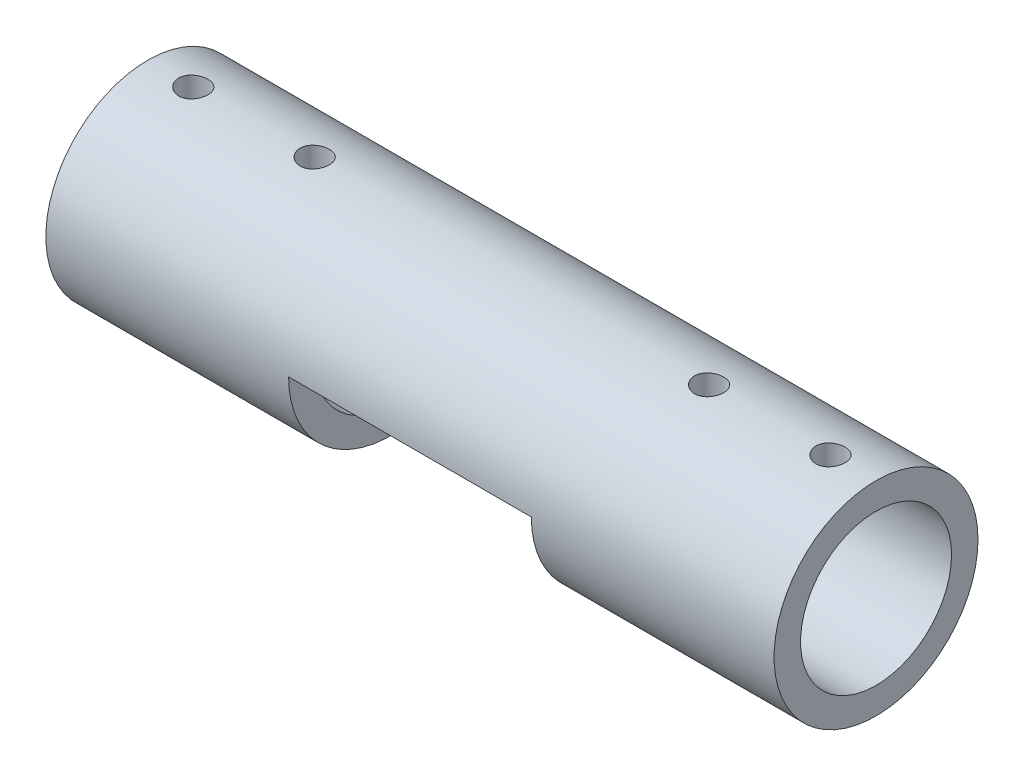
SolidWorks part; units mm, degrees
ref_plane "Front Plane" through (0, 0, 0) normal (0, 0, 1) x (1, 0, 0)
ref_plane "Top Plane" through (0, 0, 0) normal (0, 1, 0) x (1, 0, 0)
ref_plane "Right Plane" through (0, 0, 0) normal (1, 0, 0) x (0, 0, -1)
sketch "Sketch1" plane through (0, 0, 0) normal (1, 0, 0) x (0, 0, -1)
  circle A0 centre (0, 0) radius 10.668
  circle A1 centre (0, 0) radius 7.8994
  dimension "D2" = 15.7988
  dimension "D1" = 21.336
extrude "MainBody" add sketch "Sketch1" along normal blind 76.2
sketch "Sketch2" plane through (0, 0, 0) normal (0, 1, 0) x (1, 0, 0)
  line L1 (25.4, 12.7) -> (50.8, 12.7)
  line L2 (25.4, 12.7) -> (25.4, -12.7)
  line L3 (25.4, -12.7) -> (50.8, -12.7)
  line L4 (50.8, 12.7) -> (50.8, -12.7)
  point P7 (38.1, 12.7)
  point P8 (50.8, 0)
  dimension "D3" = 38.1
  dimension "D4" = 25.4
  dimension "D5" = 25.4
extrude "CoaxEntry" cut sketch "Sketch2" against normal up to surface up to face at (76.2, 0, -10.668)
sketch "Sketch3" plane through (0, 0, 0) normal (0, 1, 0) x (1, 0, 0)
  line L0 (76.2, -10.668) -> (76.2, 10.668) construction
  circle A0 centre (4.7625, 0) radius 1.524
  circle A2 centre (17.4625, 0) radius 1.524
  circle A3 centre (71.4375, 0) radius 1.524
  circle A4 centre (58.7375, 0) radius 1.524
  point P3 (0, 0)
  dimension "D1" = 3.048
  dimension "D2" = 4.7625
  dimension "D4" = 12.7
  dimension "D5" = 4.7625
  dimension "D3" = 2
extrude "AntennaMountHoles" cut sketch "Sketch3" along normal through all
equation "\"OD\" = 0.84in'Outer Diameter of PVC (1/2in Sch 40)"
equation "\"D1@Sketch1\"=\"OD\""
equation "\"ID\" = 0.622in'Inner Diameter of PCV (1/2in Sch 40)"
equation "\"D2@Sketch1\"=\"ID\""
equation "\"PVC_Len\" = 3in'Length of PVC to make connector"
equation "\"D1@MainBody\" = \"PVC_Len\""
equation "\"Max_Coax_Diam\"=1"
equation "\"ScrewDiam\"=0.12"
equation "\"D1@Sketch3\"=\"ScrewDiam\""
equation "\"AntennaScrew_Inset\"=0.1875"
equation "\"D2@Sketch3\"=\"AntennaScrew_Inset\""
equation "\"D5@Sketch3\"=\"AntennaScrew_Inset\""
equation "\"D3@Sketch2\"=\"PVC_Len\"/2"
equation "\"D4@Sketch2\"=\"Max_Coax_Diam\""
equation "\"D5@Sketch2\"=\"Max_Coax_Diam\""
